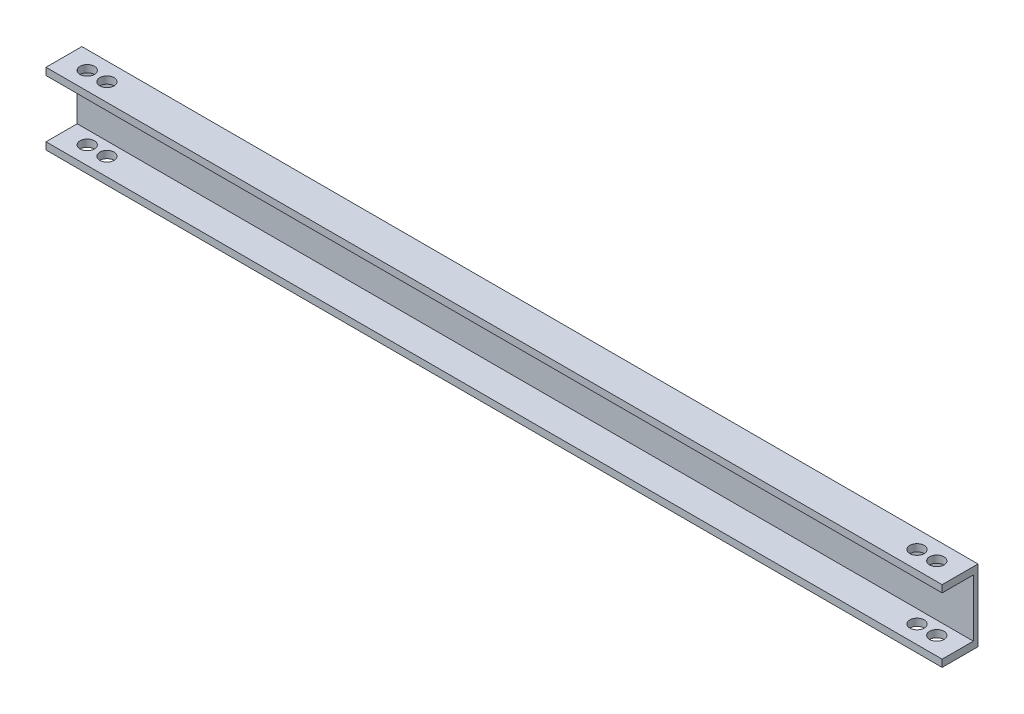
SolidWorks part; units mm, degrees
ref_plane "Front Plane" through (0, 0, 0) normal (0, 0, 1) x (1, 0, 0)
ref_plane "Top Plane" through (0, 0, 0) normal (0, 1, 0) x (1, 0, 0)
ref_plane "Right Plane" through (0, 0, 0) normal (1, 0, 0) x (0, 0, -1)
sketch "Sketch1" plane through (0, 0, 0) normal (0, 1, 0) x (1, 0, 0)
  line L1 (-317.5, -12.7) -> (317.5, -12.7)
  line L2 (-317.5, -12.7) -> (-317.5, 12.7)
  line L3 (-317.5, 12.7) -> (317.5, 12.7)
  line L4 (317.5, -12.7) -> (317.5, 12.7)
  line L5 (-317.5, -12.7) -> (317.5, 12.7) construction
  line L6 (-317.5, 12.7) -> (317.5, -12.7) construction
  point P0 (0, 0)
  dimension "D1" = 635
extrude "Boss-Extrude1" add sketch "Sketch1" along normal blind 50.8
sketch "Sketch2" plane through (0, 50.8, 0) normal (0, 1, 0) x (1, 0, 0)
  circle A0 centre (-300.99, 0) radius 5.08
  circle A1 centre (-287.02, 0) radius 5.08
  circle A2 centre (300.99, 0) radius 5.08
  circle A3 centre (287.02, 0) radius 5.08
  point P8 (0, 0)
  point P9 (0, 0)
  point P10 (0, 0)
  point P11 (0, 0)
extrude "Cut-Extrude1" cut sketch "Sketch2" against normal blind 53.34
sketch "Sketch3" plane through (0, 0, 12.7) normal (0, 0, 1) x (1, 0, 0)
  line L0 (-317.5, 50.8) -> (-317.5, 0) construction
  line L1 (-317.5, 45.72) -> (317.5, 45.72)
  line L2 (-317.5, 45.72) -> (-317.5, 5.08)
  line L3 (-317.5, 5.08) -> (317.5, 5.08)
  line L4 (317.5, 45.72) -> (317.5, 5.08)
  line L5 (317.5, 50.8) -> (317.5, 0) construction
extrude "Cut-Extrude2" cut sketch "Sketch3" against normal blind 22.098
